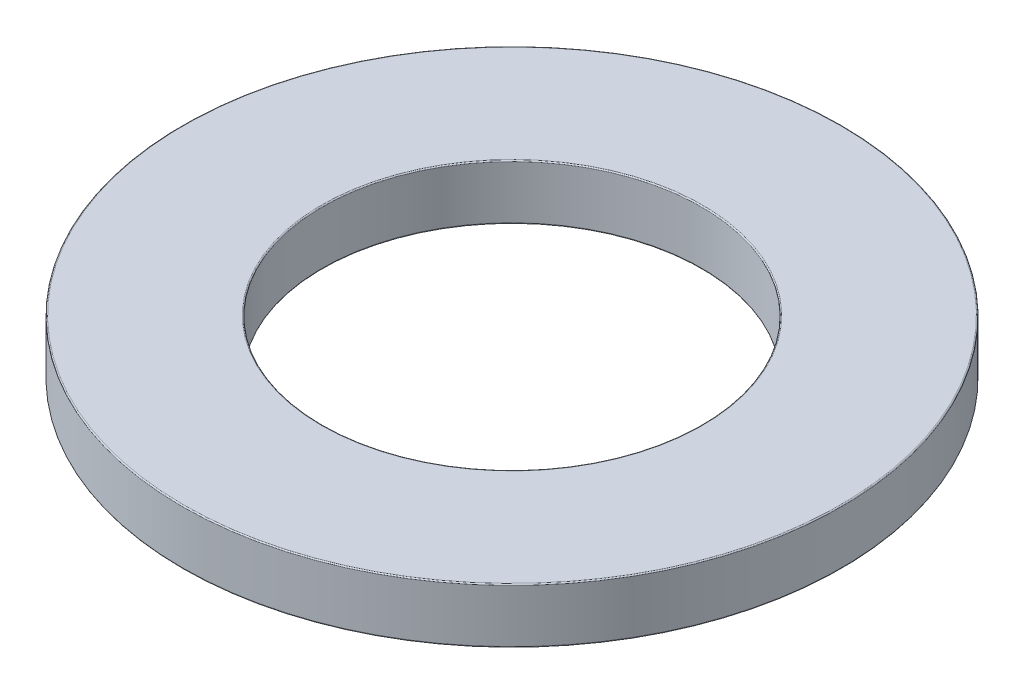
SolidWorks part; units mm, degrees
ref_plane "Front Plane" through (0, 0, 0) normal (0, 0, 1) x (1, 0, 0)
ref_plane "Top Plane" through (0, 0, 0) normal (0, 1, 0) x (1, 0, 0)
ref_plane "Right Plane" through (0, 0, 0) normal (1, 0, 0) x (0, 0, -1)
sketch "Sketch1" plane through (0, 0, 0) normal (0, 1, 0) x (1, 0, 0)
  circle A0 centre (0, 0) radius 4.6355
  circle A1 centre (0, 0) radius 2.667
  point P4 (2.667, 0)
  point P5 (0, 4.6355)
  point P6 (0, -4.6355)
  point P7 (-2.667, 0)
  dimension "OD" = 9.271
  dimension "ID" = 5.334
sketch "Sketch2" plane through (0, 0, 0) normal (1, 0, 0) x (0, 0, -1)
  line L1 (-4.6355, -0.3873) -> (4.6355, -0.3873)
  line L2 (-4.6355, -0.3873) -> (-4.6355, 0.3874)
  line L3 (-4.6355, 0.3874) -> (4.6355, 0.3874)
  line L4 (4.6355, -0.3873) -> (4.6355, 0.3874)
  line L5 (-4.6355, -0.3873) -> (4.6355, 0.3874) construction
  line L6 (-4.6355, 0.3874) -> (4.6355, -0.3873) construction
  point P0 (0, 0)
  dimension "Thickness" = 0.7747
sketch "Sketch3" plane through (0, 0, 0) normal (0, 1, 0) x (1, 0, 0)
  circle A1 centre (0, 0) radius 2.667
  circle A2 centre (0, 0) radius 2.667
  circle A3 centre (0, 0) radius 4.6355
  circle A4 centre (0, 0) radius 4.6355
  dimension "D1" = 0
  dimension "D2" = 0
extrude "Boss-Extrude1" add sketch "Sketch3" along normal mid plane 0.7747
fillet "Fillet1" radius 0.0159 4 edges at (0, -0.3873, 2.667) (0, 0.3873, 2.667) (0, -0.3873, 4.6355) (0, 0.3873, 4.6355)
equation "\"D1@Boss-Extrude1\" = \"Thickness@Sketch2\""
